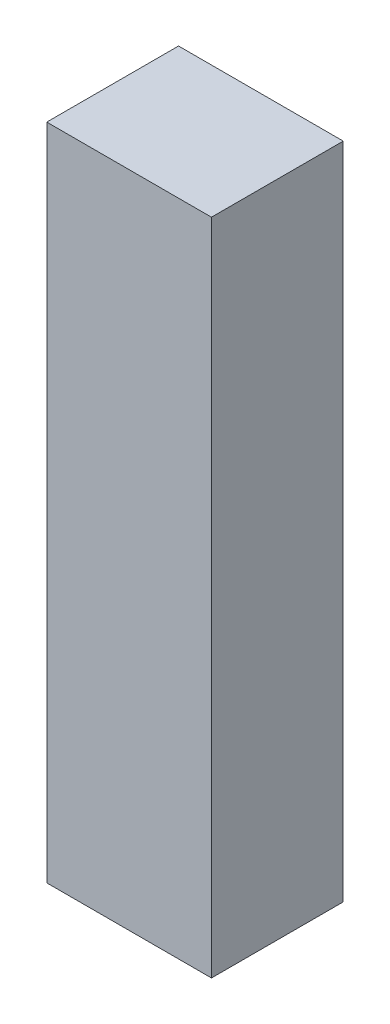
SolidWorks part; units mm, degrees
ref_plane "Front Plane" through (0, 0, 0) normal (0, 0, 1) x (1, 0, 0)
ref_plane "Top Plane" through (0, 0, 0) normal (0, 1, 0) x (1, 0, 0)
ref_plane "Right Plane" through (0, 0, 0) normal (1, 0, 0) x (0, 0, -1)
other "Configuration Table"
sketch "Sketch1" plane through (0, 0, 0) normal (0, 0, 1) x (1, 0, 0)
  line L1 (360, 330) -> (410, 330)
  line L2 (360, 330) -> (360, 530)
  line L3 (360, 530) -> (410, 530)
  line L4 (410, 330) -> (410, 530)
extrude "TOPPING_arka_duvar_pano_surucu_4_1" add sketch "Sketch1" against normal blind 40 from offset 736 separate body
